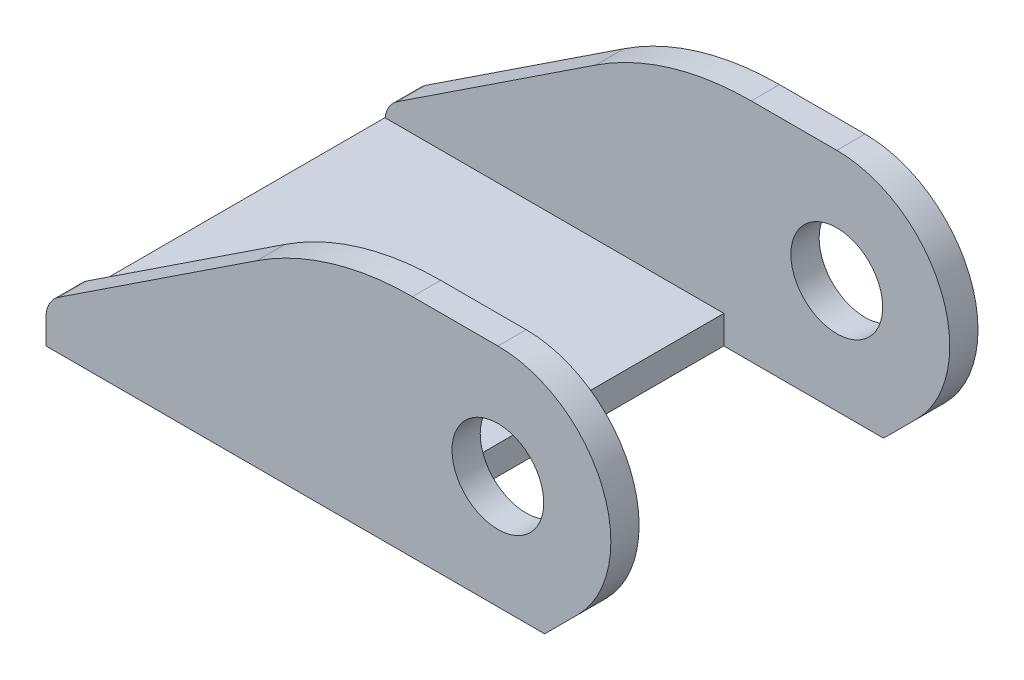
SolidWorks part; units mm, degrees
ref_plane "Front Plane" through (0, 0, 0) normal (0, 0, 1) x (1, 0, 0)
ref_plane "Top Plane" through (0, 0, 0) normal (0, 1, 0) x (1, 0, 0)
ref_plane "Right Plane" through (0, 0, 0) normal (1, 0, 0) x (0, 0, -1)
sketch "Sketch1" plane through (0, 0, 0) normal (0, 1, 0) x (1, 0, 0)
  line L1 (-20, 8) -> (20, 8)
  line L2 (-20, 8) -> (-20, -8)
  line L3 (-20, -8) -> (20, -8)
  line L4 (20, 8) -> (20, -8)
  line L5 (-20, 8) -> (20, -8) construction
  line L6 (-20, -8) -> (20, 8) construction
  point P0 (0, 0)
sketch "Sketch3" plane through (0, 0, 0) normal (0, 0, 1) x (1, 0, 0)
  line L0 (-20, 0) -> (20, 0) construction
  line L1 (-12, 0) -> (12, 0)
  line L2 (-20, 0) -> (-20, 16) construction
  line L3 (-12, 16) -> (12, 16)
  line L5 (-20, 0) -> (20, 0) construction
  line L6 (-20, 8) -> (-12, 8) construction
  line L7 (20, 8) -> (12, 8) construction
  arc A0 (-12, 16) -> (-12, 0) centre (-12, 8) ccw
  arc A1 (12, 0) -> (12, 16) centre (12, 8) ccw
ref_plane "Plane1" through (0, 0, 9) normal (0, 0, 1) x (1, 0, 0)
sketch "Sketch6" plane through (0, 0, 0) normal (0, 1, 0) x (1, 0, 0)
  line L0 (0, 0) -> (0, -9) construction
  line L1 (-20, -13) -> (20, -13)
  line L2 (-20, -13) -> (-20, -11)
  line L3 (20, -9) -> (20, -11) construction
  line L4 (-20, -11) -> (20, -11)
  line L5 (0, -11) -> (0, -13) construction
  line L6 (20, -13) -> (20, -11)
  line L10 (1, -11.5) -> (1, -13) construction
  line L11 (-20, -11) -> (-20, -9) construction
  line L12 (-20, -9) -> (20, -9) construction
extrude "Boss-Extrude4" add sketch "Sketch6" along normal blind 16
sketch "Sketch8" plane through (0, 0, 11) normal (0, 0, -1) x (-1, 0, 0)
  circle A1 centre (12, 8) radius 2.6
sketch "Sketch9" plane through (0, 0, 11) normal (0, 0, -1) x (-1, 0, 0)
  circle A0 centre (-12, 8) radius 3.25
extrude "Cut-Extrude2" cut sketch "Sketch9" against normal blind 2
sketch "Sketch7" plane through (0, 0, 11) normal (0, 0, -1) x (-1, 0, 0)
  line L0 (-5.942, 16) -> (-12, 16)
  line L1 (-15.3137, 0) -> (20, 0)
  line L2 (-17.6569, 2.3431) -> (-15.3137, 0)
  line L3 (21.3543, 17.091) -> (-21.3543, 17.091)
  line L4 (21.3543, 17.091) -> (21.3543, -1.091)
  line L5 (21.3543, -1.091) -> (-21.3543, -1.091)
  line L6 (-21.3543, 17.091) -> (-21.3543, -1.091)
  line L7 (21.3543, 17.091) -> (-21.3543, -1.091) construction
  line L8 (21.3543, -1.091) -> (-21.3543, 17.091) construction
  line L9 (20, 0) -> (20, 1.7672)
  line L10 (19.1015, 3.4366) -> (5.0731, 12.6933)
  line L11 (-0.0619, 0) -> (-0.0619, 3.8657) construction
  arc A0 (-12, 16) -> (-17.6569, 2.3431) centre (-12, 8) ccw
  arc A1 (5.0731, 12.6933) -> (-5.942, 16) centre (-5.942, -4) ccw
  circle A2 centre (-12, 8) radius 3.25 construction
  arc A3 (20, 1.7672) -> (19.1015, 3.4366) centre (18, 1.7672) ccw
  circle A4 centre (-12, 8) radius 2.6 construction
  circle A5 centre (-12, 8) radius 3.25 construction
  point P6 (0, 8)
  point P18 (20, 2.8437)
  point P20 (0.0619, 16)
extrude "Cut-Extrude1" cut sketch "Sketch7" along normal through all and the other way blind 16
mirror "Mirror2" about plane through (0, 0, 0) normal (0, 0, 1) of bodies 117 109
sketch "Sketch12" plane through (0, 0, 0) normal (0, 1, 0) x (1, 0, 0)
  line L0 (-19.1015, -13) -> (-5.0731, -13) construction
  line L3 (-20, -13) -> (3.9999, -13)
  line L4 (3.9999, 13) -> (3.9999, -13)
  line L8 (-20, 13) -> (-20, -13)
  line L10 (-3, 0) -> (3.9999, -0.0162) construction
  line L14 (-20, 13) -> (3.9999, 13)
  line L15 (-20, 0) -> (-13, 0) construction
  line L16 (-13, 0) -> (-3, 0) construction
  line L18 (6.9942, -0.0231) -> (13.9942, -0.0231) construction
  circle A0 centre (-13, 0) radius 1.75
  circle A1 centre (-3, 0) radius 1.75
extrude "Boss-Extrude8" add sketch "Sketch12" along normal blind 2
